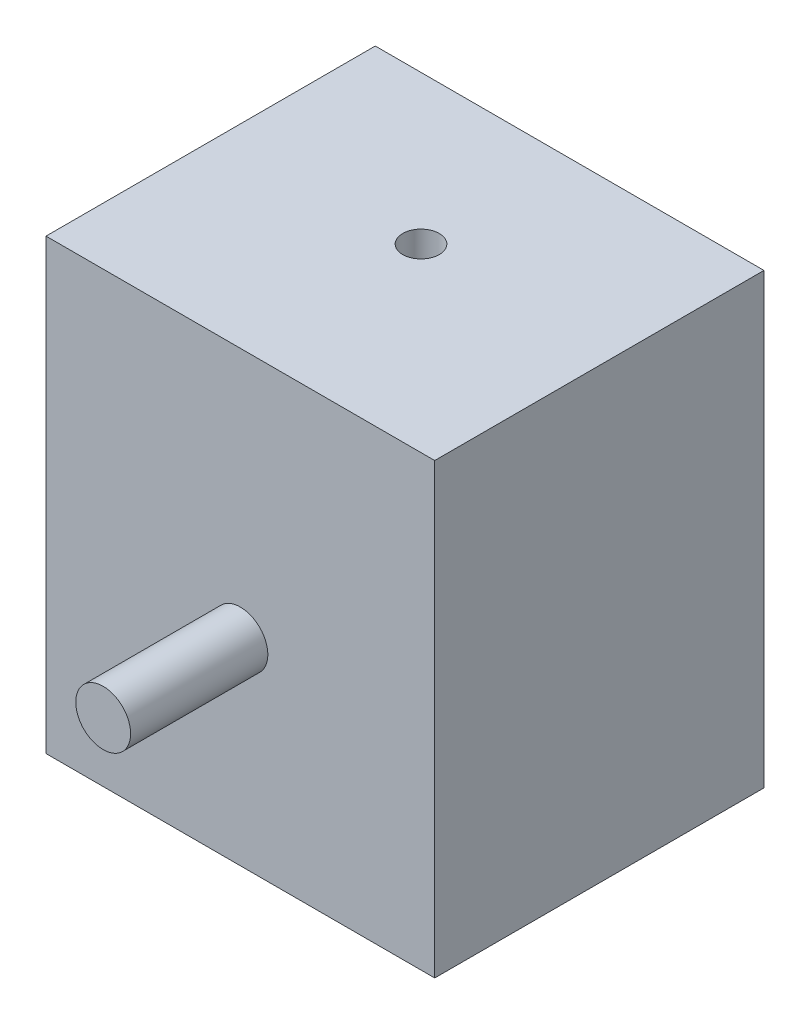
SolidWorks part; units mm, degrees
ref_plane "Front Plane" through (0, 0, 0) normal (0, 0, 1) x (1, 0, 0)
ref_plane "Top Plane" through (0, 0, 0) normal (0, 1, 0) x (1, 0, 0)
ref_plane "Right Plane" through (0, 0, 0) normal (1, 0, 0) x (0, 0, -1)
sketch "Sketch1" plane through (0, 0, 0) normal (0, 1, 0) x (1, 0, 0)
  line L1 (-42.5, 36) -> (42.5, 36)
  line L2 (-42.5, 36) -> (-42.5, -36)
  line L3 (-42.5, -36) -> (42.5, -36)
  line L4 (42.5, 36) -> (42.5, -36)
  line L5 (-42.5, 36) -> (42.5, -36) construction
  line L6 (-42.5, -36) -> (42.5, 36) construction
  point P0 (0, 0)
extrude "Boss-Extrude1" add sketch "Sketch1" along normal blind 98
sketch "Sketch2" plane through (0, 98, 0) normal (0, 1, 0) x (1, 0, 0)
  line L0 (42.5, 36) -> (-42.5, 36) construction
  circle A0 centre (0, 3.5) radius 4
  dimension "D1" = 32.5
extrude "Cut-Extrude1" cut sketch "Sketch2" against normal blind 10
sketch "Sketch3" plane through (0, 0, 36) normal (0, 0, 1) x (1, 0, 0)
  line L0 (-42.5, 0) -> (42.5, 0) construction
  circle A0 centre (0, 43) radius 6
  dimension "D1" = 43
extrude "Boss-Extrude2" add sketch "Sketch3" along normal blind 30
